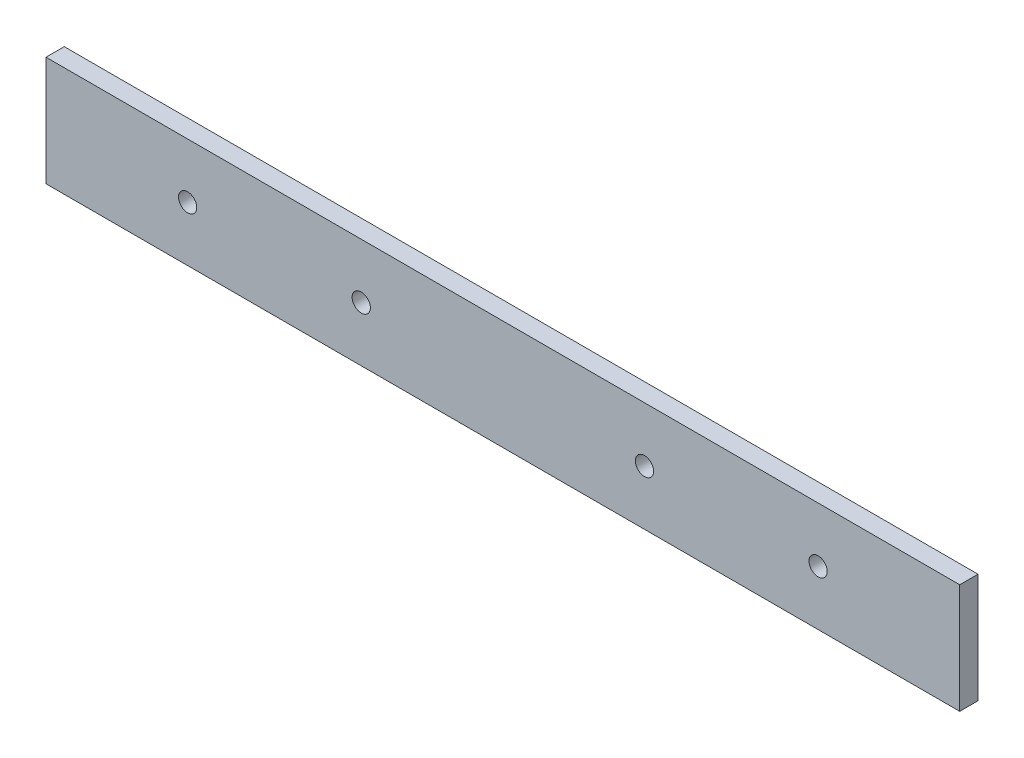
SolidWorks part; units mm, degrees
material "Plain Carbon Steel"
ref_plane "Front Plane" through (0, 0, 0) normal (0, 0, 1) x (1, 0, 0)
ref_plane "Top Plane" through (0, 0, 0) normal (0, 1, 0) x (1, 0, 0)
ref_plane "Right Plane" through (0, 0, 0) normal (1, 0, 0) x (0, 0, -1)
sketch "Sketch1" plane through (0, 0, 0) normal (0, 0, 1) x (1, 0, 0)
  line L0 (0, 0) -> (0, 62.1742) construction
  line L1 (-250, -30) -> (250, -30)
  line L2 (-250, -30) -> (-250, 30)
  line L3 (-250, 30) -> (250, 30)
  line L4 (250, -30) -> (250, 30)
  line L5 (-250, -30) -> (250, 30) construction
  line L6 (-250, 30) -> (250, -30) construction
  line L7 (0, 0) -> (250, 0) construction
  line L8 (125, 0) -> (125, 55.2949) construction
  circle A0 centre (172.5, 0) radius 5
  circle A1 centre (77.5, 0) radius 5
  circle A2 centre (-172.5, 0) radius 5
  circle A3 centre (-77.5, 0) radius 5
  point P0 (0, 0)
  dimension "D3" = 10
  dimension "D4" = 72.5
  dimension "D6" = 145
  dimension "D5" = 85
  dimension "D1" = 500
  dimension "D2" = 60
extrude "Boss-Extrude1" add sketch "Sketch1" along normal mid plane 10
